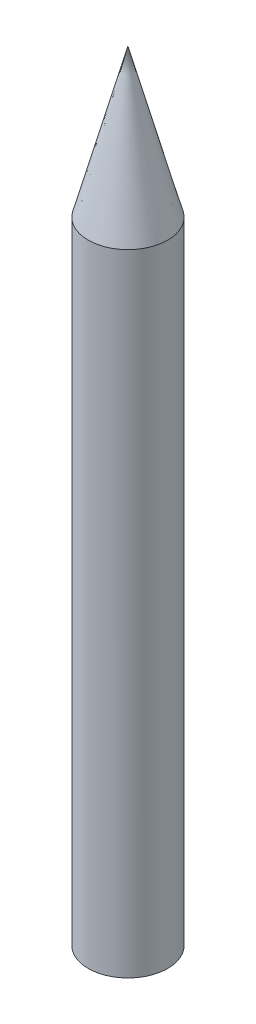
SolidWorks part; units mm, degrees
material "Nickel silver 65-12, UNS C75700"
ref_plane "Front" through (0, 0, 0) normal (0, 0, 1) x (1, 0, 0)
ref_plane "Top" through (0, 0, 0) normal (0, 1, 0) x (1, 0, 0)
ref_plane "Right" through (0, 0, 0) normal (1, 0, 0) x (0, 0, -1)
sketch "Sketch1" plane through (0, 0, 0) normal (1, 0, 0) x (0, 0, -1)
  line L12 (0, 0) -> (0, -10)
  line L13 (0, -10) -> (0.51, -10)
  line L14 (0.51, -10) -> (0.51, -1.9033)
  line L15 (0.51, -1.9033) -> (0, 0)
  dimension "D1" = 15
  dimension "D2" = 0.51
  dimension "D3" = 10
revolve "Revolve1" add sketch "Sketch1" angle 360 about L12
equation "\"D2@Sketch1\"=1.02/2"
